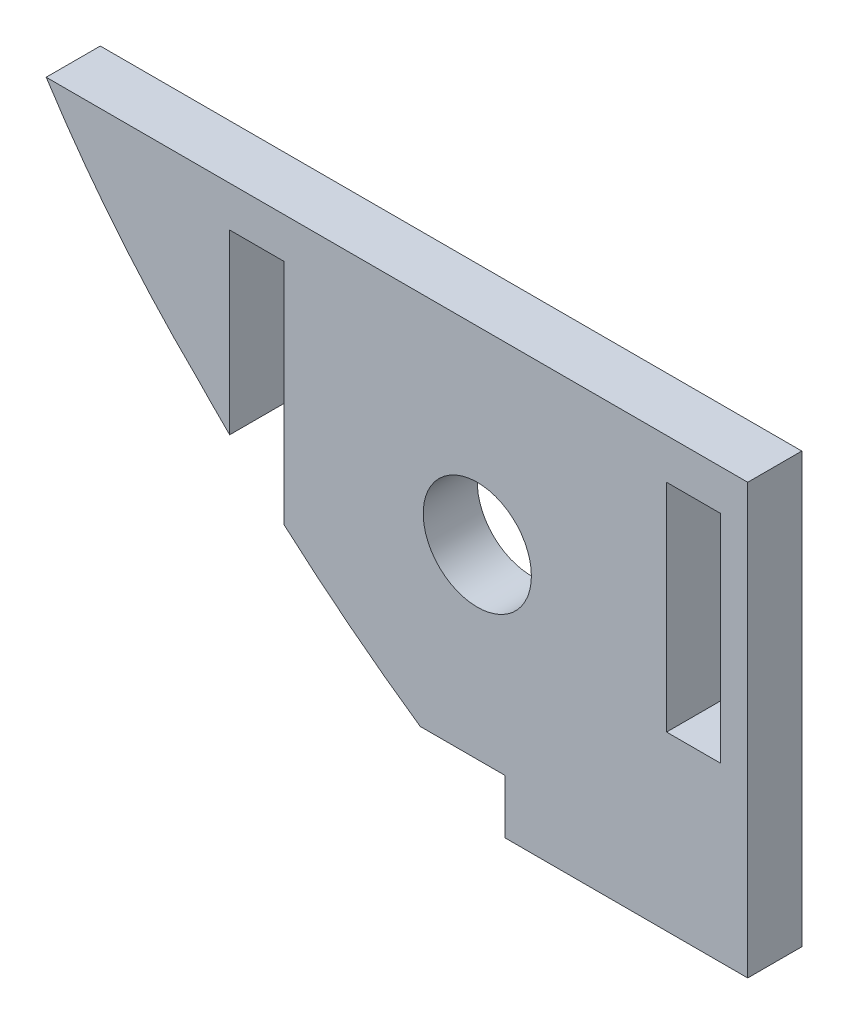
SolidWorks part; units mm, degrees
ref_plane "Front Plane" through (0, 0, 0) normal (0, 0, 1) x (1, 0, 0)
ref_plane "Top Plane" through (0, 0, 0) normal (0, 1, 0) x (1, 0, 0)
ref_plane "Right Plane" through (0, 0, 0) normal (1, 0, 0) x (0, 0, -1)
sketch "Sketch1" plane through (0, 0, 0) normal (0, 0, 1) x (1, 0, 0)
  line L0 (-6.6541, -12.7061) -> (-6.6541, -10.7061)
  line L1 (-23.6167, 3.1696) -> (2.3245, 3.1696)
  line L2 (-9.7836, -10.7061) -> (-6.6541, -10.7061)
  line L3 (1.3245, 1.6696) -> (1.3245, -6.3304)
  line L4 (1.3245, -6.3304) -> (-0.6755, -6.3304)
  line L5 (2.3245, 3.1696) -> (2.3245, -12.7061)
  line L6 (-0.6755, -6.3304) -> (-0.6755, 1.6696)
  line L7 (-0.6755, 1.6696) -> (1.3245, 1.6696)
  line L8 (-6.6541, -12.7061) -> (2.3245, -12.7061)
  line L14 (-14.8318, 1.6696) -> (-14.8318, -6.7543)
  line L19 (-16.8318, -4.8895) -> (-16.8318, 1.6696)
  line L22 (-16.8318, 1.6696) -> (-14.8318, 1.6696)
  arc A0 (-23.6167, 3.1696) -> (-18, -3.7061) centre (8.865, 23.9719) ccw
  arc A1 (-18, -3.7061) -> (-16.8318, -4.8895) centre (20.321, 32.9518) ccw
  circle A2 centre (-7.6755, -3.8304) radius 2
  arc A3 (-14.8318, -6.7543) -> (-9.7836, -10.7061) centre (20.321, 32.9518) ccw
  dimension "D1" = 4
  dimension "D2" = 2
  dimension "D4" = 7
  dimension "D6" = 2
  dimension "D7" = 8
  dimension "D8" = 1
extrude "Boss-Extrude1" add sketch "Sketch1" along normal blind 2
